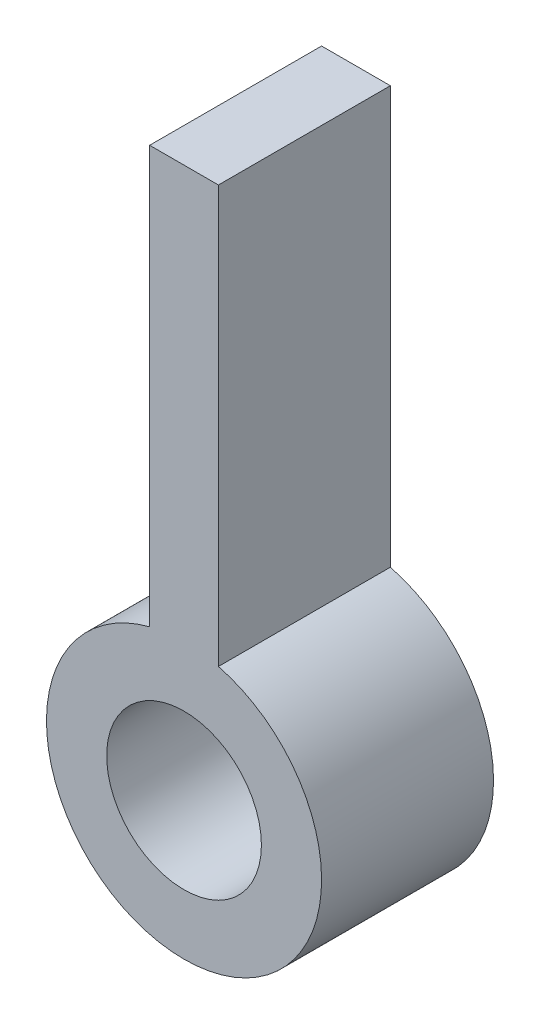
SolidWorks part; units mm, degrees
ref_plane "Front Plane" through (0, 0, 0) normal (1, 0, 0) x (0, 1, 0)
ref_plane "Top Plane" through (0, 0, 0) normal (0, 0, 1) x (0, 1, 0)
ref_plane "Right Plane" through (0, 0, 0) normal (0, 1, 0) x (-1, 0, 0)
sketch "Sketch2" plane through (0, 0, 0) normal (0, 0, 1) x (0, 1, 0)
  line L6 (3.873, 1) -> (16, 1)
  line L8 (3.873, -1) -> (16, -1)
  line L9 (16, 1) -> (16, -1)
  circle A3 centre (0, 0) radius 2.25
  arc A4 (3.873, 1) -> (3.873, -1) centre (0, 0) ccw
  dimension "D1" = 4.5
  dimension "D2" = 8
  dimension "D3" = 12.127
  dimension "D4" = 2
  dimension "D6" = 16
extrude "Boss-Extrude2" add sketch "Sketch2" along normal blind 5
